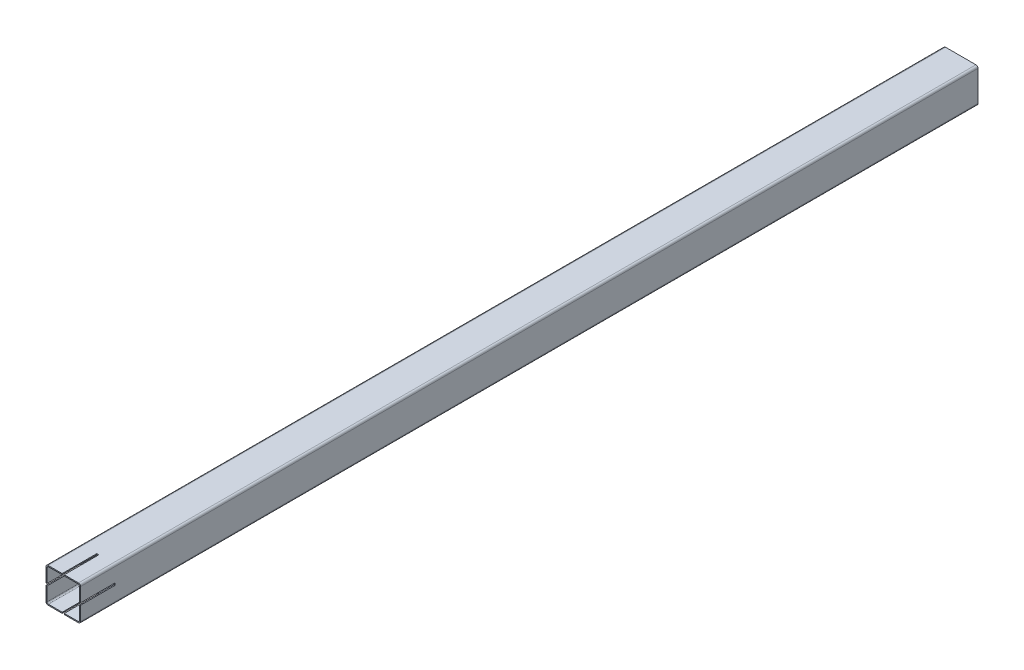
SolidWorks part; units mm, degrees
material "AISI 1020"
ref_plane "Спереди" through (0, 0, 0) normal (0, 0, 1) x (1, 0, 0)
ref_plane "Сверху" through (0, 0, 0) normal (0, 1, 0) x (1, 0, 0)
ref_plane "Справа" through (0, 0, 0) normal (1, 0, 0) x (0, 0, -1)
sketch "Эскиз1" plane through (0, 0, 0) normal (0, 0, 1) x (1, 0, 0)
  line B0 (-44, 50) -> (44, 50)
  line B1 (-50, 44) -> (-50, -44)
  line B2 (-44, -50) -> (44, -50)
  line B3 (50, 44) -> (50, -44)
  line B4 (-50, 50) -> (50, -50) construction
  line B5 (-50, -50) -> (50, 50) construction
  line B6 (-43, 47) -> (43, 47)
  line B7 (-47, 43) -> (-47, -43)
  line B8 (-43, -47) -> (43, -47)
  line B9 (47, 43) -> (47, -43)
  line B10 (-47, 47) -> (47, -47) construction
  line B11 (-47, -47) -> (47, 47) construction
  arc B12 (-50, -44) -> (-44, -50) centre (-44, -44) ccw
  arc B13 (44, -50) -> (50, -44) centre (44, -44) ccw
  arc B14 (44, 50) -> (50, 44) centre (44, 44) cw
  arc B15 (-44, 50) -> (-50, 44) centre (-44, 44) ccw
  arc B16 (-47, -43) -> (-43, -47) centre (-43, -43) ccw
  arc B17 (43, -47) -> (47, -43) centre (43, -43) ccw
  arc B18 (43, 47) -> (47, 43) centre (43, 43) cw
  arc B19 (-43, 47) -> (-47, 43) centre (-43, 43) ccw
sketch_block_instance "Блок1-1"
sketch_block "Блок1" parameters "D3"=6, "D4"=4, "D1"=100, "D2"=3
extrude "Бобышка-Вытянуть1" add sketch "Эскиз1" against normal blind 2600
sketch "Эскиз2" plane through (0, 0, 0) normal (0, 0, 1) x (1, 0, 0)
  line L0 (-50, 44) -> (-50, -44) construction
  line L1 (-50, 3) -> (-3, 3)
  line L2 (-50, 3) -> (-50, -3)
  line L3 (-50, -3) -> (-3, -3)
  line L4 (50, 3) -> (50, -3)
  line L5 (50, -44) -> (50, 44) construction
  line L6 (44, 50) -> (-44, 50) construction
  line L7 (-3, 50) -> (3, 50)
  line L8 (-3, 50) -> (-3, 3)
  line L9 (-3, -50) -> (3, -50)
  line L10 (3, 50) -> (3, 3)
  line L11 (-44, -50) -> (44, -50) construction
  line L12 (3, 3) -> (50, 3)
  line L13 (3, -3) -> (50, -3)
  line L14 (-3, -3) -> (-3, -50)
  line L15 (3, -3) -> (3, -50)
  point P16 (0, -50)
  point P18 (50, 0)
  dimension "D1" = 6
extrude "Вырез-Вытянуть1" cut sketch "Эскиз2" against normal blind 100
